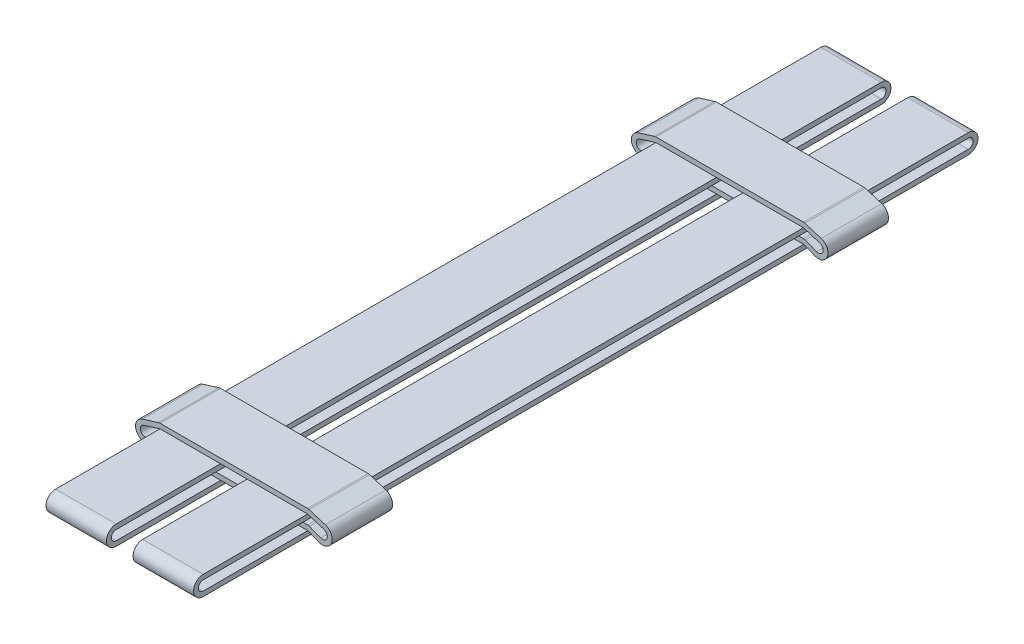
SolidWorks part; units mm, degrees
material "SBR"
ref_plane "Front Plane" through (0, 0, 0) normal (0, 0, 1) x (1, 0, 0)
ref_plane "Top Plane" through (0, 0, 0) normal (0, 1, 0) x (1, 0, 0)
ref_plane "Right Plane" through (0, 0, 0) normal (1, 0, 0) x (0, 0, -1)
sketch "Sketch1" plane through (0, 0, 0) normal (1, 0, 0) x (0, 0, -1)
  line L0 (-158.15, 0) -> (158.15, 0) construction
  line L1 (-158.15, 2) -> (158.15, 2)
  line L2 (-158.15, -2) -> (158.15, -2)
  arc A0 (-158.15, 2) -> (-158.15, -2) centre (-158.15, 0) ccw
  arc A1 (158.15, -2) -> (158.15, 2) centre (158.15, 0) ccw
  point P2 (0, 0)
  dimension "D2" = 2
  dimension "D1" = 316.3
extrude "Extrude-Thin1" add sketch "Sketch1" along normal blind 25 from offset 5.5 thin thin type one direction wall 2
mirror "Mirror3" about plane through (0, 0, 0) normal (1, 0, 0) of bodies 101
sketch "Sketch3" plane through (0, 0, 0) normal (0, 0, 1) x (1, 0, 0)
  line L0 (35.9251, -1.864) -> (31.2249, -0.036)
  line L1 (30.5, 0.1) -> (-30.5, 0.1)
  line L3 (37.2421, 1.9103) -> (30.5, 4)
  line L4 (30.5, 4) -> (-30.5, 4)
  line L5 (36.65, 0) -> (30.5, 0) construction
  line L7 (0, 0.1) -> (0, 0) construction
  line L8 (-35.9251, -1.864) -> (-31.2249, -0.036)
  line L9 (-37.2421, 1.9103) -> (-30.5, 4)
  line L10 (30.5, -2) -> (30.5, 2) construction
  arc A0 (37.2421, 1.9103) -> (35.9251, -1.864) centre (36.65, 0) cw
  arc A1 (31.2249, -0.036) -> (30.5, 0.1) centre (30.5, -1.9) ccw
  arc A3 (-31.2249, -0.036) -> (-30.5, 0.1) centre (-30.5, -1.9) cw
  arc A4 (-37.2421, 1.9103) -> (-35.9251, -1.864) centre (-36.65, 0) ccw
  point P28 (0, 4)
  dimension "D1" = 2
  dimension "D2" = 2
  dimension "D3" = 73.3
  dimension "D4" = 5.9
extrude "Extrude-Thin2" add sketch "Sketch3" along normal blind 25 from offset 90 separate body thin
fillet "Fillet1" radius 2 2 edges at (-30.8028, 6, 102.5) (30.8028, 6, 102.5)
mirror "Mirror4" about plane through (0, 0, 0) normal (0, 0, 1) of bodies 104
